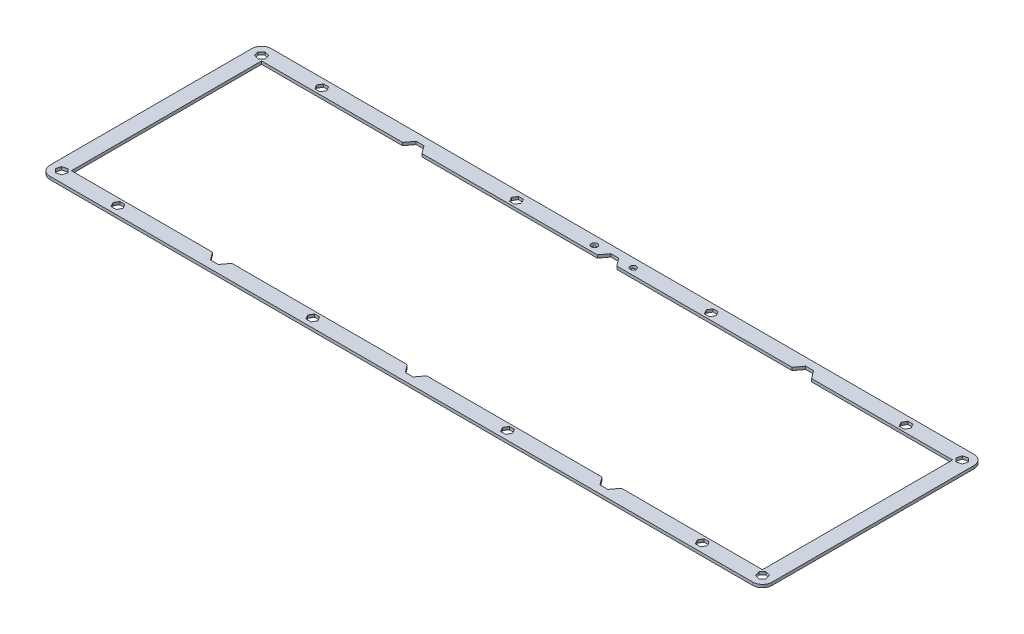
SolidWorks part; units mm, degrees
ref_plane "Front Plane" through (0, 0, 0) normal (0, 0, 1) x (1, 0, 0)
ref_plane "Top Plane" through (0, 0, 0) normal (0, 1, 0) x (1, 0, 0)
ref_plane "Right Plane" through (0, 0, 0) normal (1, 0, 0) x (0, 0, -1)
sketch "Sketch1" plane through (0, 0, 0) normal (0, 1, 0) x (1, 0, 0)
  line L0 (0, 108.6) -> (0, 5)
  line L1 (365.775, 0) -> (5, 0)
  line L2 (370.775, 108.6) -> (370.775, 5)
  line L3 (365.775, 113.6) -> (5, 113.6)
  line L4 (8, 8) -> (8, 105.6)
  line L5 (362.775, 8) -> (362.775, 105.6)
  line L6 (8, 105.6) -> (80.3875, 105.6)
  line L7 (90.3875, 105.6) -> (180.3875, 105.6)
  line L8 (280.3875, 105.6) -> (283.3875, 109.6)
  line L9 (283.3875, 109.6) -> (287.3875, 109.6)
  line L10 (290.3875, 105.6) -> (287.3875, 109.6)
  line L11 (362.775, 105.6) -> (290.3875, 105.6)
  line L12 (280.3875, 105.6) -> (190.3875, 105.6)
  line L13 (8, 8) -> (80.3875, 8)
  line L14 (90.3875, 8) -> (180.3875, 8)
  line L15 (362.775, 8) -> (290.3875, 8)
  line L16 (280.3875, 8) -> (190.3875, 8)
  line L17 (180.3875, 105.6) -> (183.3875, 109.6)
  line L18 (183.3875, 109.6) -> (187.3875, 109.6)
  line L19 (190.3875, 105.6) -> (187.3875, 109.6)
  line L20 (80.3875, 105.6) -> (83.3875, 109.6)
  line L21 (83.3875, 109.6) -> (87.3875, 109.6)
  line L22 (90.3875, 105.6) -> (87.3875, 109.6)
  line L23 (280.3875, 8) -> (283.3875, 4)
  line L24 (283.3875, 4) -> (287.3875, 4)
  line L25 (290.3875, 8) -> (287.3875, 4)
  line L26 (180.3875, 8) -> (183.3875, 4)
  line L27 (183.3875, 4) -> (187.3875, 4)
  line L28 (190.3875, 8) -> (187.3875, 4)
  line L29 (80.3875, 8) -> (83.3875, 4)
  line L30 (83.3875, 4) -> (87.3875, 4)
  line L31 (90.3875, 8) -> (87.3875, 4)
  line L32 (234.0885, 111.35) -> (236.6865, 111.35)
  line L33 (236.6865, 111.35) -> (237.9856, 109.1)
  line L34 (237.9856, 109.1) -> (236.6865, 106.85)
  line L35 (236.6865, 106.85) -> (234.0885, 106.85)
  line L36 (234.0885, 106.85) -> (232.7894, 109.1)
  line L37 (232.7894, 109.1) -> (234.0885, 111.35)
  line L38 (334.0885, 111.35) -> (336.6865, 111.35)
  line L39 (336.6865, 111.35) -> (337.9856, 109.1)
  line L40 (337.9856, 109.1) -> (336.6865, 106.85)
  line L41 (336.6865, 106.85) -> (334.0885, 106.85)
  line L42 (334.0885, 106.85) -> (332.7894, 109.1)
  line L43 (332.7894, 109.1) -> (334.0885, 111.35)
  line L44 (365.9474, 110.6095) -> (367.7846, 108.7724)
  line L45 (367.7846, 108.7724) -> (367.1121, 106.2629)
  line L46 (367.1121, 106.2629) -> (364.6026, 105.5905)
  line L47 (364.6026, 105.5905) -> (362.7655, 107.4276)
  line L48 (362.7655, 107.4276) -> (363.4379, 109.9371)
  line L49 (363.4379, 109.9371) -> (365.9474, 110.6095)
  line L50 (136.6865, 111.35) -> (134.0885, 111.35)
  line L51 (134.0885, 111.35) -> (132.7894, 109.1)
  line L52 (132.7894, 109.1) -> (134.0885, 106.85)
  line L53 (134.0885, 106.85) -> (136.6865, 106.85)
  line L54 (136.6865, 106.85) -> (137.9856, 109.1)
  line L55 (137.9856, 109.1) -> (136.6865, 111.35)
  line L56 (36.6865, 111.35) -> (34.0885, 111.35)
  line L57 (34.0885, 111.35) -> (32.7894, 109.1)
  line L58 (32.7894, 109.1) -> (34.0885, 106.85)
  line L59 (34.0885, 106.85) -> (36.6865, 106.85)
  line L60 (36.6865, 106.85) -> (37.9856, 109.1)
  line L61 (37.9856, 109.1) -> (36.6865, 111.35)
  line L62 (4.8276, 110.6095) -> (2.9905, 108.7724)
  line L63 (2.9905, 108.7724) -> (3.6629, 106.2629)
  line L64 (3.6629, 106.2629) -> (6.1724, 105.5905)
  line L65 (6.1724, 105.5905) -> (8.0096, 107.4276)
  line L66 (8.0096, 107.4276) -> (7.3371, 109.9371)
  line L67 (7.3371, 109.9371) -> (4.8276, 110.6095)
  line L68 (234.0885, 2.25) -> (236.6865, 2.25)
  line L69 (236.6865, 2.25) -> (237.9856, 4.5)
  line L70 (237.9856, 4.5) -> (236.6865, 6.75)
  line L71 (236.6865, 6.75) -> (234.0885, 6.75)
  line L72 (234.0885, 6.75) -> (232.7894, 4.5)
  line L73 (232.7894, 4.5) -> (234.0885, 2.25)
  line L74 (334.0885, 2.25) -> (336.6865, 2.25)
  line L75 (336.6865, 2.25) -> (337.9856, 4.5)
  line L76 (337.9856, 4.5) -> (336.6865, 6.75)
  line L77 (336.6865, 6.75) -> (334.0885, 6.75)
  line L78 (334.0885, 6.75) -> (332.7894, 4.5)
  line L79 (332.7894, 4.5) -> (334.0885, 2.25)
  line L80 (365.9474, 2.9905) -> (367.7846, 4.8276)
  line L81 (367.7846, 4.8276) -> (367.1121, 7.3371)
  line L82 (367.1121, 7.3371) -> (364.6026, 8.0095)
  line L83 (364.6026, 8.0095) -> (362.7655, 6.1724)
  line L84 (362.7655, 6.1724) -> (363.4379, 3.6629)
  line L85 (363.4379, 3.6629) -> (365.9474, 2.9905)
  line L86 (136.6865, 2.25) -> (134.0885, 2.25)
  line L87 (134.0885, 2.25) -> (132.7894, 4.5)
  line L88 (132.7894, 4.5) -> (134.0885, 6.75)
  line L89 (134.0885, 6.75) -> (136.6865, 6.75)
  line L90 (136.6865, 6.75) -> (137.9856, 4.5)
  line L91 (137.9856, 4.5) -> (136.6865, 2.25)
  line L92 (36.6865, 2.25) -> (34.0885, 2.25)
  line L93 (34.0885, 2.25) -> (32.7894, 4.5)
  line L94 (32.7894, 4.5) -> (34.0885, 6.75)
  line L95 (34.0885, 6.75) -> (36.6865, 6.75)
  line L96 (36.6865, 6.75) -> (37.9856, 4.5)
  line L97 (37.9856, 4.5) -> (36.6865, 2.25)
  line L98 (4.8276, 2.9905) -> (2.9905, 4.8276)
  line L99 (2.9905, 4.8276) -> (3.6629, 7.3371)
  line L100 (3.6629, 7.3371) -> (6.1724, 8.0095)
  line L101 (6.1724, 8.0095) -> (8.0096, 6.1724)
  line L102 (8.0096, 6.1724) -> (7.3371, 3.6629)
  line L103 (7.3371, 3.6629) -> (4.8276, 2.9905)
  arc A0 (365.775, 0) -> (370.775, 5) centre (365.775, 5) ccw
  arc A1 (370.775, 108.6) -> (365.775, 113.6) centre (365.775, 108.6) ccw
  arc A2 (0, 5) -> (5, 0) centre (5, 5) ccw
  arc A3 (5, 113.6) -> (0, 108.6) centre (5, 108.6) ccw
  circle A4 centre (175.3875, 109.1) radius 1.55
  circle A5 centre (195.3875, 109.1) radius 1.55
extrude "Boss-Extrude1" add sketch "Sketch1" against normal blind 1.5
